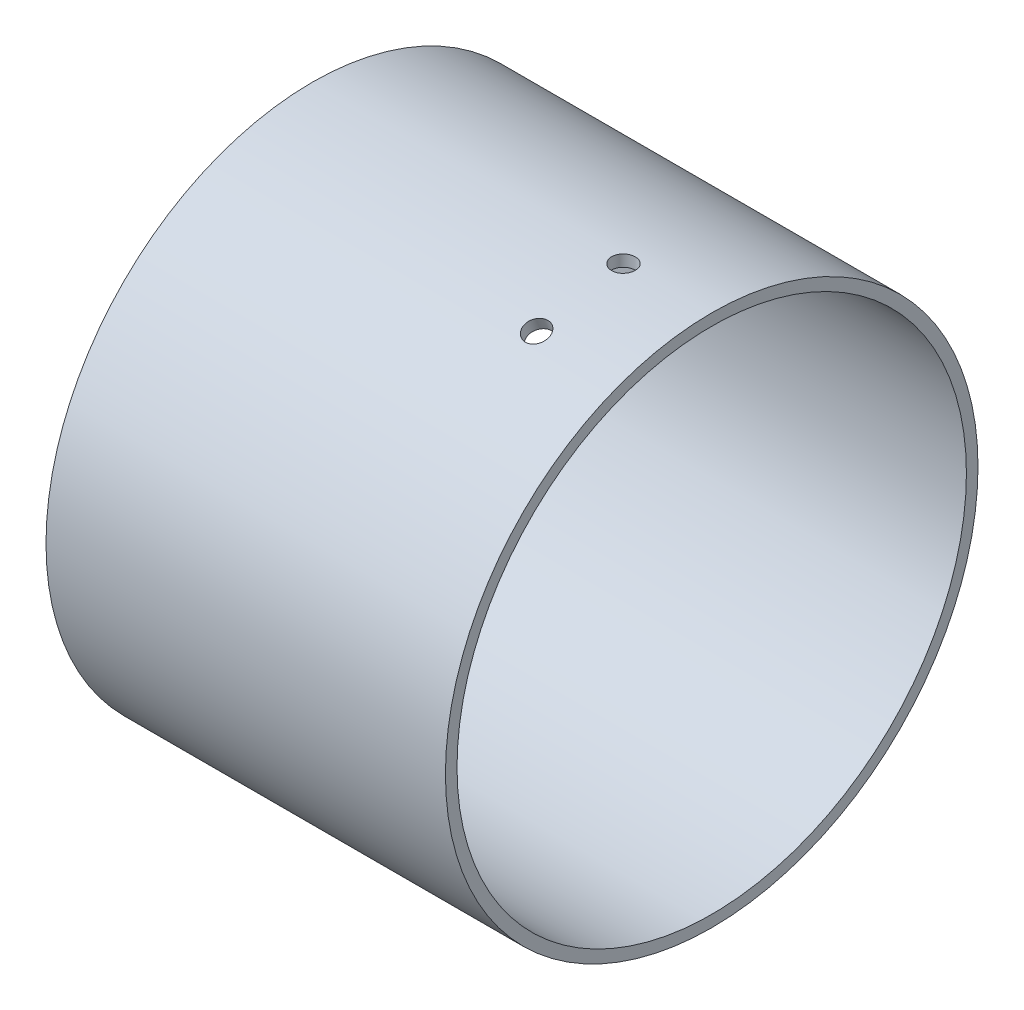
SolidWorks part; units mm, degrees
ref_plane "Front Plane" through (0, 0, 0) normal (0, 0, 1) x (1, 0, 0)
ref_plane "Top Plane" through (0, 0, 0) normal (0, 1, 0) x (1, 0, 0)
ref_plane "Right Plane" through (0, 0, 0) normal (1, 0, 0) x (0, 0, -1)
sketch "Sketch2" plane through (0, 0, 0) normal (1, 0, 0) x (0, 0, -1)
  circle A0 centre (0, 0) radius 44
  circle A1 centre (0, 0) radius 46
  dimension "D1" = 88
  dimension "D2" = 92
extrude "Boss-Extrude1" add sketch "Sketch2" along normal blind 69
hole_wizard "#20 (0.161) Diameter Hole1" positions "3DSketch3" profile "Sketch5" hole size "#20" standard "ANSI Inch"
sketch3d "3DSketch3"
  line L2 (54, 45.9994, 0.2367) -> (0, 45.9994, 0.2367)
  line L3 (54, 43.3976, 15.2529) -> (0, 43.3976, 15.2529)
  circle A0 centre (0, 0, 0) radius 46 construction
  point P1 (54, 45.9994, 0.2367)
  point P3 (54, 43.3976, 15.2529)
  point P12 (46, 0, 0)
  point P17 (27, 43.3976, 15.2529)
  dimension "D1" = 15.24
  dimension "D2" = 54
  dimension "D3" = 54
sketch "Sketch5" plane through (54, 45.9994, 0.2367) normal (1, 0, 0) x (0, -0.0051, 1)
  line L0 (0, 0) -> (0, 2)
  line L1 (0, 2) -> (2.0447, 2)
  line L2 (2.0447, 2) -> (2.0447, 0)
  line L5 (2.0447, 0) -> (0, 0)
  line L11 (0, -6.35) -> (0, 107.95) construction
  dimension "Thru Hole Dia." = 4.0894
  dimension "Thru Hole Depth" = 2
